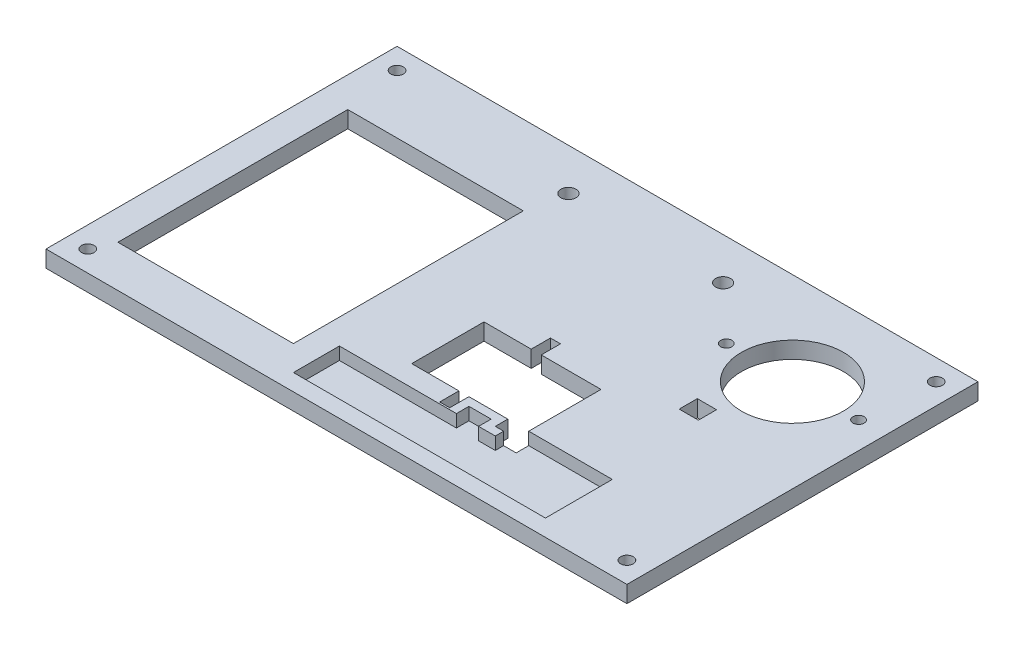
SolidWorks part; units mm, degrees
ref_plane "Front Plane" through (0, 0, 0) normal (0, 0, 1) x (1, 0, 0)
ref_plane "Top Plane" through (0, 0, 0) normal (0, 1, 0) x (1, 0, 0)
ref_plane "Right Plane" through (0, 0, 0) normal (1, 0, 0) x (0, 0, -1)
sketch "Sketch1" plane through (0, 0, 0) normal (0, 1, 0) x (1, 0, 0)
  line L0 (-15.621, -53.34) -> (15.621, -53.34)
  line L1 (-88.265, -53.34) -> (-15.621, -53.34)
  line L2 (-88.265, -53.34) -> (-88.265, 53.34)
  line L3 (-88.265, 53.34) -> (88.265, 53.34)
  line L4 (88.265, -53.34) -> (88.265, 53.34)
  line L5 (-88.265, -53.34) -> (88.265, 53.34) construction
  line L6 (-88.265, 53.34) -> (88.265, -53.34) construction
  line L9 (15.621, -53.34) -> (88.265, -53.34)
  point P0 (0, 0)
  point P9 (0, -53.34)
  dimension "D1" = 106.68
  dimension "D2" = 176.53
  dimension "D4" = 31.242
extrude "Boss-Extrude1" add sketch "Sketch1" along normal blind 5.08
sketch "Sketch3" plane through (0, 5.08, 0) normal (0, 1, 0) x (1, 0, 0)
  line L0 (-81.915, 53.34) -> (-81.915, 40.64) construction
  line L1 (-88.265, 53.34) -> (-75.565, 53.34) construction
  line L2 (-88.265, 53.34) -> (-88.265, 40.64) construction
  line L3 (-88.265, 40.64) -> (-75.565, 40.64) construction
  line L4 (-75.565, 53.34) -> (-75.565, 40.64) construction
  circle A0 centre (-81.915, 46.99) radius 1.905
  dimension "D3" = 3.81
  dimension "D1" = 12.7
  dimension "D2" = 12.7
extrude "Cut-Extrude1" cut sketch "Sketch3" against normal through all
sketch "Sketch4" plane through (0, 5.08, 0) normal (0, 1, 0) x (1, 0, 0)
  line L0 (88.265, 53.34) -> (75.565, 53.34) construction
  line L1 (88.265, 53.34) -> (-88.265, 53.34) construction
  line L2 (75.565, 53.34) -> (75.565, 40.64) construction
  line L3 (75.565, 40.64) -> (88.265, 40.64) construction
  line L4 (88.265, -53.34) -> (88.265, 53.34) construction
  line L5 (88.265, 40.64) -> (88.265, 53.34) construction
  line L6 (88.265, 53.34) -> (75.565, 40.64) construction
  line L7 (-88.265, -53.34) -> (-88.265, -40.64) construction
  line L8 (-88.265, 53.34) -> (-88.265, -53.34) construction
  line L9 (-88.265, -40.64) -> (-75.565, -40.64) construction
  line L10 (-75.565, -40.64) -> (-75.565, -53.34) construction
  line L11 (-88.265, -53.34) -> (88.265, -53.34) construction
  line L12 (-75.565, -53.34) -> (-88.265, -53.34) construction
  line L13 (-88.265, -53.34) -> (-75.565, -40.64) construction
  line L14 (88.265, -53.34) -> (88.265, -40.64) construction
  line L15 (88.265, -40.64) -> (75.565, -40.64) construction
  line L16 (75.565, -40.64) -> (75.565, -53.34) construction
  line L17 (-88.265, -53.34) -> (88.265, -53.34) construction
  line L18 (75.565, -53.34) -> (88.265, -53.34) construction
  line L19 (88.265, -53.34) -> (75.565, -40.64) construction
  line L20 (0, 0) -> (0, 53.34) construction
  line L21 (-23.495, 40.64) -> (23.495, 40.64) construction
  circle A0 centre (81.915, 46.99) radius 1.905
  circle A1 centre (-81.915, -46.99) radius 1.905
  circle A2 centre (81.915, -46.99) radius 1.905
  circle A4 centre (23.495, 40.64) radius 2.286
  circle A5 centre (-23.495, 40.64) radius 2.286
  point P37 (0, 40.64)
  dimension "D3" = 3.81
  dimension "D6" = 3.81
  dimension "D9" = 3.81
  dimension "D10" = 4.572
  dimension "." = 4.572
  dimension "D1" = 12.7
  dimension "D2" = 12.7
  dimension "D4" = 12.7
  dimension "D5" = 12.7
  dimension "D7" = 12.7
  dimension "D8" = 12.7
  dimension "D12" = 12.7
  dimension "D13" = 46.99
extrude "Cut-Extrude2" cut sketch "Sketch4" against normal through all
sketch "Sketch5" plane through (0, 0, 0) normal (0, -1, 0) x (1, 0, 0)
  line L0 (0, 0) -> (0, 5.969) construction
  line L2 (-2.54, 27.94) -> (-2.54, 5.969)
  line L3 (-2.54, 5.969) -> (11.811, 5.969)
  line L4 (33.02, 29.21) -> (33.02, 5.969)
  line L10 (25.8092, 27.94) -> (26.67, 27.94)
  line L12 (-88.265, 53.34) -> (88.265, 53.34) construction
  line L13 (-2.54, 27.94) -> (11.811, 27.94)
  line L14 (11.811, 5.969) -> (11.811, 0.127)
  line L15 (11.811, 33.782) -> (14.859, 33.782)
  line L16 (11.811, 33.782) -> (11.811, 27.94)
  line L17 (11.811, 0.127) -> (14.859, 0.127)
  line L18 (14.859, 33.782) -> (14.859, 27.94)
  line L19 (14.859, 5.969) -> (14.859, 0.127)
  line L20 (14.859, 27.94) -> (25.8092, 27.94)
  line L21 (14.859, 5.969) -> (33.02, 5.969)
  line L22 (14.859, 27.94) -> (14.859, 5.969) construction
  line L25 (33.02, 29.21) -> (33.02, 31.75)
  line L26 (33.02, 31.75) -> (26.67, 31.75)
  line L27 (26.67, 27.94) -> (26.67, 31.75)
  dimension "D1" = 2.54
  dimension "D2" = 35.56
  dimension "D3" = 23.241
  dimension "D4" = 18.161
  dimension "D5" = 5.842
  dimension "D6" = 25.4
  dimension "D7" = 3.048
  dimension "D8" = 5.842
  dimension "D9" = 2.54
  dimension "D10" = 6.35
  dimension "15" = 3.81
extrude "Cut-Extrude3" cut sketch "Sketch5" against normal through all
sketch "Sketch6" plane through (0, 5.08, 0) normal (0, 1, 0) x (1, 0, 0)
  line L0 (60.071, 3.3528) -> (60.071, 46.9392) construction
  line L1 (44.577, 25.146) -> (75.565, 25.146) construction
  line L2 (88.265, -53.34) -> (88.265, 53.34) construction
  circle A0 centre (60.071, 25.146) radius 15.494
  circle A3 centre (39.9778, 25.146) radius 1.7
  circle A5 centre (80.1642, 25.146) radius 1.7
  point P2 (0, 0)
  point P3 (0, 0)
  point P14 (60.071, 3.3528)
  point P15 (60.071, 3.3528)
  point P17 (60.071, 25.146)
  point P19 (60.071, 25.146)
  point P20 (60.071, 3.3528)
  point P21 (60.0694, 3.3503)
  point P31 (60.071, 25.146)
  dimension "D1" = 30.988
  dimension "D5" = 3.4
  dimension "D6" = 3.4
  dimension "D7" = 40.1864
  dimension "D2" = 12.7
  dimension "D4" = 43.5864
extrude "Cut-Extrude4" cut sketch "Sketch6" against normal through all
sketch "Sketch7" plane through (0, 5.08, 0) normal (0, 1, 0) x (1, 0, 0)
  line L0 (-25.781, 40.64) -> (-25.781, -53.34) construction
  line L1 (-88.265, -53.34) -> (88.265, -53.34) construction
  line L3 (-25.781, 29.21) -> (-79.121, 29.21)
  line L4 (-25.781, 29.21) -> (-25.781, -40.64)
  line L5 (-25.781, -40.64) -> (-79.121, -40.64)
  line L6 (-79.121, 29.21) -> (-79.121, -40.64)
  circle A0 centre (-23.495, 40.64) radius 2.286 construction
  dimension "D1" = 12.7
  dimension "D2" = 69.85
  dimension "D3" = 53.34
extrude "Cut-Extrude5" cut sketch "Sketch7" against normal through all
sketch "Sketch8" plane through (0, 5.08, 0) normal (0, 1, 0) x (1, 0, 0)
  line L1 (50.0725, 6.2439) -> (55.911, 6.2439)
  line L2 (50.0725, 6.2439) -> (50.0725, 0.7298)
  line L3 (50.0725, 0.7298) -> (55.911, 0.7298)
  line L4 (55.911, 6.2439) -> (55.911, 0.7298)
extrude "Cut-Extrude6" cut sketch "Sketch8" against normal through all
sketch "Sketch9" plane through (0, 5.08, 0) normal (0, 1, 0) x (1, 0, 0)
  line L1 (29.21, -27.94) -> (58.42, -27.94)
  line L2 (29.21, -27.94) -> (29.21, -34.29)
  line L5 (32.5525, -48.26) -> (58.42, -48.26)
  line L6 (29.21, -34.29) -> (24.13, -34.29)
  line L8 (32.5525, -48.26) -> (-18.161, -48.26)
  line L9 (-18.161, -34.29) -> (-18.161, -48.26)
  line L11 (17.399, -34.29) -> (17.399, -30.48)
  line L12 (17.399, -30.48) -> (24.13, -30.48)
  line L13 (24.13, -34.29) -> (24.13, -30.48)
  line L14 (58.42, -27.94) -> (58.42, -48.26)
  line L15 (17.399, -34.29) -> (-18.161, -34.29)
  line L16 (14.859, -27.94) -> (14.859, -33.782) construction
  line L17 (26.67, -27.94) -> (14.859, -27.94) construction
  line L18 (26.67, -31.75) -> (26.67, -27.94) construction
  line L19 (33.02, -31.75) -> (26.67, -31.75) construction
  line L20 (33.02, -5.969) -> (33.02, -31.75) construction
  point P17 (20.7645, -27.94)
  point P20 (26.67, -29.845)
  point P23 (0, 0)
  dimension "D1" = 2.54
  dimension "D2" = 2.54
  dimension "D3" = 2.54
  dimension "D4" = 2.54
  dimension "D5" = 3.81
  dimension "D6" = 29.21
  dimension "D7" = 35.56
  dimension "D8" = 13.97
  dimension "D9" = 3.81
extrude "Cut-Extrude7" cut sketch "Sketch9" against normal blind 3.81
